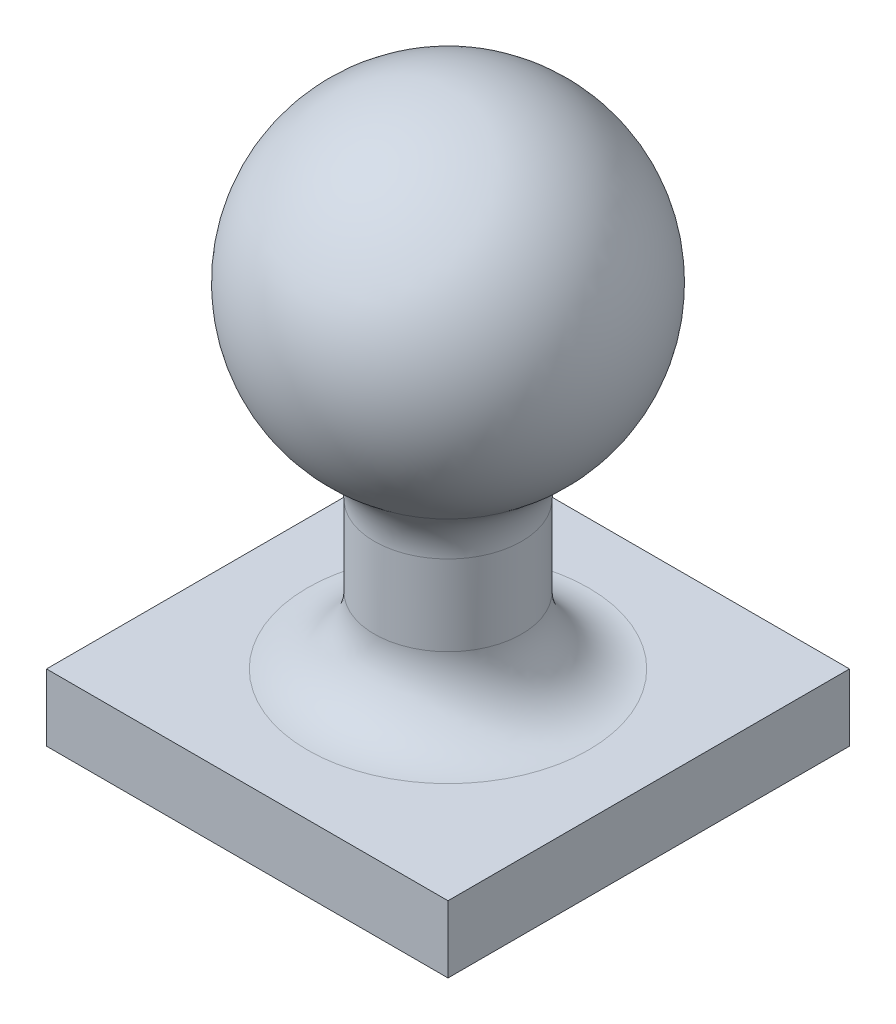
SolidWorks part; units mm, degrees
other "Markup1"
sketch "Sketch7" plane through (50.8, 43.18, 0) normal (0.5774, 0.5773, 0.5774) x (0.7071, 0, -0.7071)
material "Chrome Stainless Steel"
ref_plane "Front Plane" through (0, 0, 0) normal (0, 0, 1) x (1, 0, 0)
ref_plane "Top Plane" through (0, 0, 0) normal (0, 1, 0) x (1, 0, 0)
ref_plane "Right Plane" through (0, 0, 0) normal (1, 0, 0) x (0, 0, -1)
sketch "Sketch2" plane through (0, 0, 0) normal (0, 1, 0) x (1, 0, 0)
  line L0 (0, 30.48) -> (30.48, 0) construction
  line L1 (0, 0) -> (30.48, 0)
  line L2 (0, 0) -> (0, 30.48)
  line L3 (0, 30.48) -> (30.48, 30.48)
  line L4 (30.48, 0) -> (30.48, 30.48)
  point P5 (0, 0)
  point P6 (40.5345, 47.5924)
  point P7 (23.2171, 29.1109)
  point P8 (15.24, 15.24)
  point P9 (23.7992, 52.9282)
  point P10 (91.3677, 53.0192)
  point P11 (0, 0)
  point P12 (0, 0)
  point P13 (0, 0)
  point P14 (74.0166, 63.8322)
  point P15 (79.0459, 48.5767)
  point P16 (55.5758, 46.6488)
  dimension "D1" = 30.48
  dimension "D2" = 30.48
extrude "Boss-Extrude1" add sketch "Sketch2" along normal blind 5.08
sketch "Sketch3" plane through (0, 5.08, 0) normal (0, 1, 0) x (1, 0, 0)
  circle A0 centre (15.24, 15.24) radius 5.588
  point P2 (0, 0)
  point P3 (62.0301, 32.8182)
  point P4 (0, 0)
  point P5 (43.1702, 22.089)
  point P6 (0, 0)
  point P7 (45.6838, 26.5096)
  dimension "D3" = 11.176
extrude "Boss-Extrude2" add sketch "Sketch3" along normal blind 25.4
sketch "Sketch6" plane through (0, 30.48, 0) normal (0, 1, 0) x (1, 0, 0)
  line L0 (15.24, 27.94) -> (15.24, 2.54)
  arc A0 (15.24, 2.54) -> (15.24, 27.94) centre (15.24, 15.24) ccw
  point P1 (0, 0)
  point P4 (45.6838, 26.5096)
  dimension "D1" = 25.4
revolve "Revolve1" add sketch "Sketch6" angle 360 about L0
fillet "Fillet1" radius 5.08 2 edges at (15.24, 19.0754, -9.652) (15.24, 5.08, -9.652)
sketch "Sketch8" plane through (0, 5.08, 0) normal (0, 1, 0) x (1, 0, 0)
